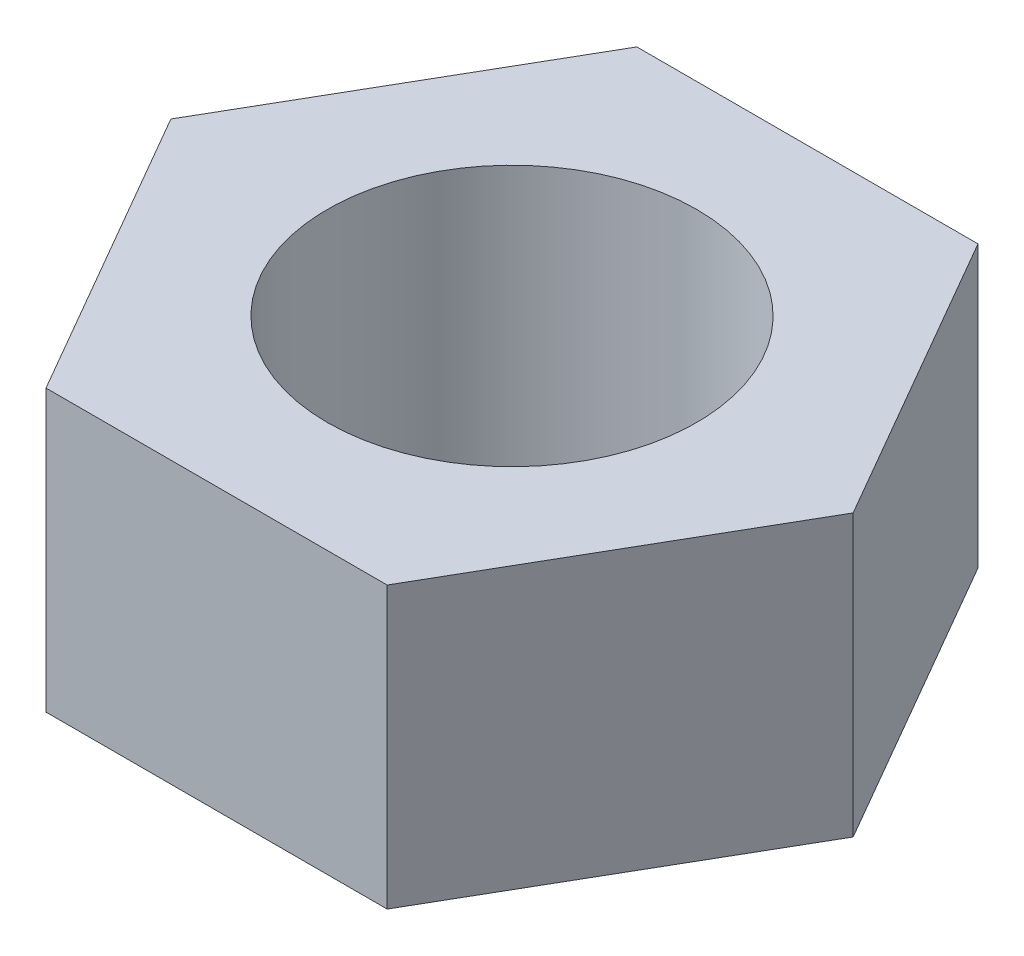
SolidWorks part; units mm, degrees
ref_plane "Front Plane" through (0, 0, 0) normal (0, 0, 1) x (1, 0, 0)
ref_plane "Top Plane" through (0, 0, 0) normal (0, 1, 0) x (1, 0, 0)
ref_plane "Right Plane" through (0, 0, 0) normal (1, 0, 0) x (0, 0, -1)
sketch "Sketch1" plane through (0, 0, 0) normal (0, 1, 0) x (1, 0, 0)
  line L1 (4.6188, 0) -> (2.3094, 4)
  line L2 (2.3094, 4) -> (-2.3094, 4)
  line L3 (-2.3094, 4) -> (-4.6188, 0)
  line L4 (-4.6188, 0) -> (-2.3094, -4)
  line L5 (-2.3094, -4) -> (2.3094, -4)
  line L6 (2.3094, -4) -> (4.6188, 0)
  circle A0 centre (0, 0) radius 4 construction
  dimension "D1" = 8
extrude "Boss-Extrude1" add sketch "Sketch1" along normal blind 3.8
sketch "Sketch2" plane through (0, 0, 0) normal (0, -1, 0) x (1, 0, 0)
  circle A0 centre (0, 0) radius 2.5
  dimension "D1" = 5
extrude "Cut-Extrude1" cut sketch "Sketch2" against normal through all
